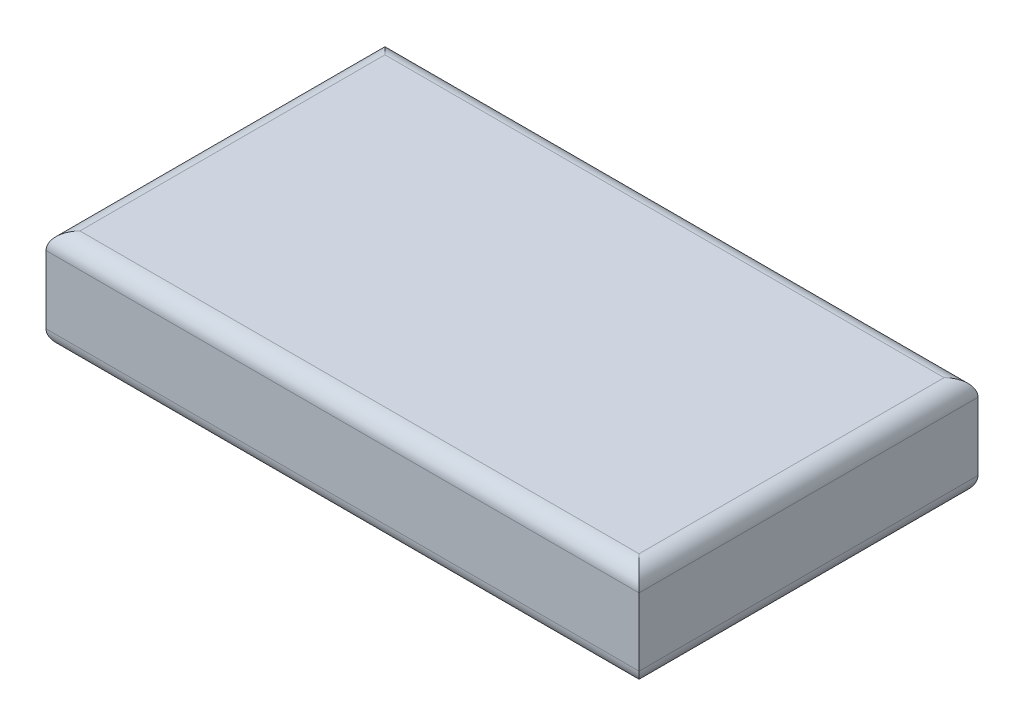
SolidWorks part; units mm, degrees
ref_plane "Front Plane" through (0, 0, 0) normal (0, 0, 1) x (1, 0, 0)
ref_plane "Top Plane" through (0, 0, 0) normal (0, 1, 0) x (1, 0, 0)
ref_plane "Right Plane" through (0, 0, 0) normal (1, 0, 0) x (0, 0, -1)
sketch "Sketch1" plane through (0, 0, 0) normal (0, 1, 0) x (1, 0, 0)
  line L1 (-17.5, 10) -> (17.5, 10)
  line L2 (-17.5, 10) -> (-17.5, -10)
  line L3 (-17.5, -10) -> (17.5, -10)
  line L4 (17.5, 10) -> (17.5, -10)
  line L5 (-17.5, 10) -> (17.5, -10) construction
  line L6 (-17.5, -10) -> (17.5, 10) construction
  point P0 (0, 0)
  dimension "D1" = 35
  dimension "D2" = 20
extrude "Boss-Extrude1" add sketch "Sketch1" along normal blind 6
fillet "Fillet1" radius 1 8 edges at (0, 0, -10) (-17.5, 0, 0) (0, 0, 10) (17.5, 0, 0) (0, 6, 10) (-17.5, 6, 0) (0, 6, -10) (17.5, 6, 0)
